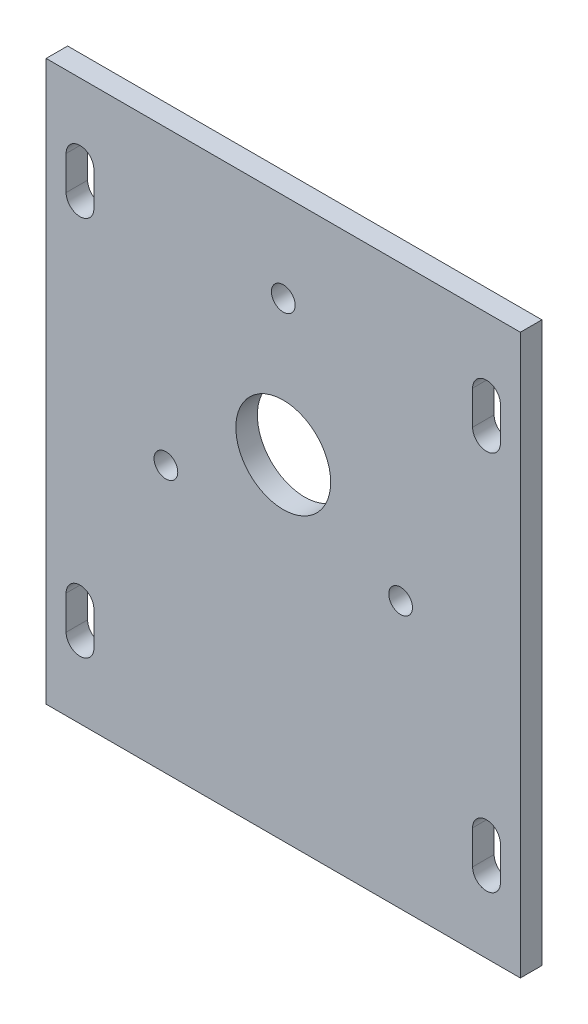
SolidWorks part; units mm, degrees
ref_plane "Front Plane" through (0, 0, 0) normal (0, 0, 1) x (1, 0, 0)
ref_plane "Top Plane" through (0, 0, 0) normal (0, 1, 0) x (1, 0, 0)
ref_plane "Right Plane" through (0, 0, 0) normal (1, 0, 0) x (0, 0, -1)
sketch "Sketch1" plane through (0, 0, 0) normal (0, 0, 1) x (1, 0, 0)
  line L0 (0, 38.1) -> (0, -38.1) construction
  line L1 (-35, -38.1) -> (35, -38.1)
  line L2 (-35, -38.1) -> (-35, 38.1)
  line L3 (-35, 38.1) -> (35, 38.1)
  line L4 (35, -38.1) -> (35, 38.1)
  line L5 (-35, -38.1) -> (35, 38.1) construction
  line L6 (-35, 38.1) -> (35, -38.1) construction
  line L7 (-35, 0) -> (35, 0) construction
  line L8 (-35, 28.1) -> (0, 28.1) construction
  line L9 (-30, 25.6) -> (-30, 30.6) construction
  line L10 (-32.05, 25.6) -> (-32.05, 30.6)
  line L11 (-27.95, 25.6) -> (-27.95, 30.6)
  line L12 (30, 25.6) -> (30, 30.6) construction
  line L13 (32.05, 25.6) -> (32.05, 30.6)
  line L14 (27.95, 25.6) -> (27.95, 30.6)
  line L15 (-30, -25.6) -> (-30, -30.6) construction
  line L16 (-32.05, -25.6) -> (-32.05, -30.6)
  line L17 (-27.95, -25.6) -> (-27.95, -30.6)
  line L18 (30, -25.6) -> (30, -30.6) construction
  line L19 (32.05, -25.6) -> (32.05, -30.6)
  line L20 (27.95, -25.6) -> (27.95, -30.6)
  circle A0 centre (-30, 28.1) radius 2.05 construction
  arc A1 (-32.05, 25.6) -> (-27.95, 25.6) centre (-30, 25.6) ccw
  arc A2 (-27.95, 30.6) -> (-32.05, 30.6) centre (-30, 30.6) ccw
  arc A3 (32.05, 25.6) -> (27.95, 25.6) centre (30, 25.6) cw
  arc A4 (27.95, 30.6) -> (32.05, 30.6) centre (30, 30.6) cw
  arc A5 (-32.05, -25.6) -> (-27.95, -25.6) centre (-30, -25.6) cw
  arc A6 (-27.95, -30.6) -> (-32.05, -30.6) centre (-30, -30.6) cw
  arc A7 (32.05, -25.6) -> (27.95, -25.6) centre (30, -25.6) ccw
  arc A8 (27.95, -30.6) -> (32.05, -30.6) centre (30, -30.6) ccw
  circle A10 centre (0, 8.1) radius 20 construction
  circle A11 centre (0, 28.1) radius 1.75
  circle A12 centre (17.3205, -1.9) radius 1.75
  circle A13 centre (-17.3205, -1.9) radius 1.75
  circle A14 centre (0, 8.1) radius 7
  circle A15 centre (0, 8.1) radius 33.35 construction
  point P0 (0, 0)
  point P16 (-30, 28.1)
  point P24 (30, 28.1)
  point P31 (-30, -28.1)
  point P38 (30, -28.1)
  point P52 (0, 8.1)
  dimension "D4" = 4.1
  dimension "D6" = 2.05
  dimension "D7" = 40
  dimension "D9" = 3.5
  dimension "D11" = 14
  dimension "D12" = 66.7
  dimension "D1" = 76.2
  dimension "D2" = 70
  dimension "D3" = 10
  dimension "D5" = 5
  dimension "D8" = 46.2
  dimension "D13" = 5
  dimension "D10" = 3
extrude "Boss-Extrude1" add sketch "Sketch1" along normal blind 3.175
sketch "Sketch3" plane through (0, 0, 3.175) normal (0, 0, 1) x (1, 0, 0)
  line L0 (0, 0) -> (62.8834, 0) construction
  line L1 (-35, 38.1) -> (35, 38.1)
  line L2 (-35, 38.1) -> (-35, 41.275)
  line L3 (-35, 41.275) -> (35, 41.275)
  line L4 (35, 38.1) -> (35, 41.275)
  line L5 (-35, -41.275) -> (35, -41.275)
  line L6 (35, -38.1) -> (35, -41.275)
  line L7 (-35, -38.1) -> (35, -38.1)
  line L8 (-35, -38.1) -> (-35, -41.275)
  dimension "D1" = 3.175
extrude "Boss-Extrude2" add sketch "Sketch3" against normal up to surface (3.175 mm away) up to face at (19.0705, -1.9, 0)
